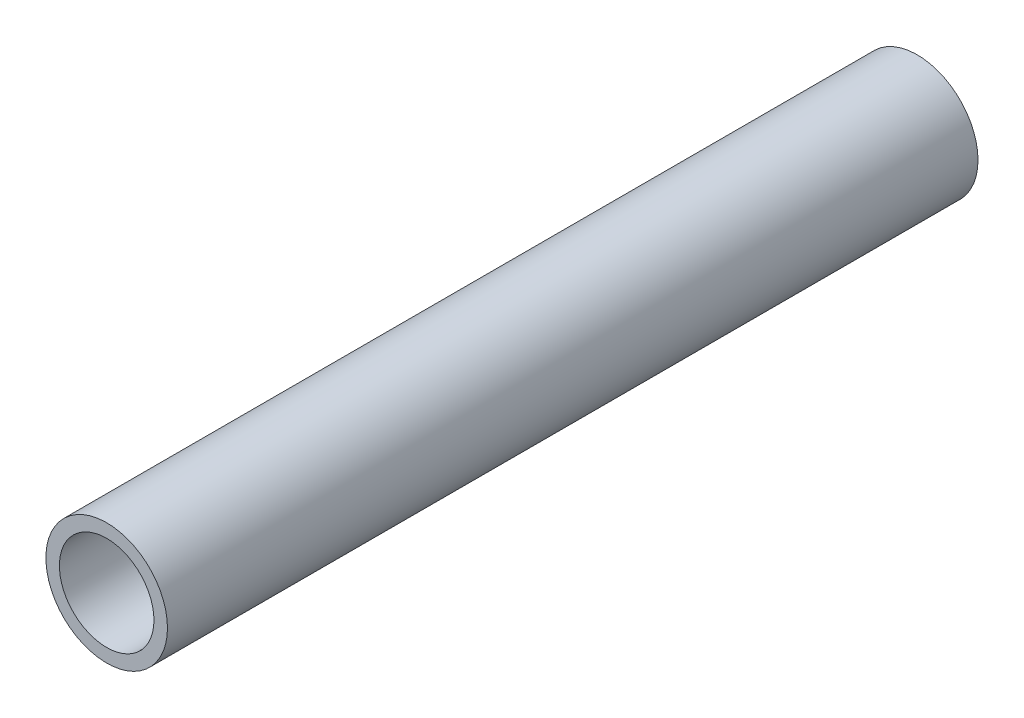
SolidWorks part; units mm, degrees
material "Copper"
ref_plane "Спереди" through (0, 0, 0) normal (0, 0, 1) x (1, 0, 0)
ref_plane "Сверху" through (0, 0, 0) normal (0, 1, 0) x (1, 0, 0)
ref_plane "Справа" through (0, 0, 0) normal (1, 0, 0) x (0, 0, -1)
sketch "Sketch1" plane through (0, 0, 0) normal (0, 0, 1) x (1, 0, 0)
  circle A0 centre (0, 0) radius 3.5
  circle A1 centre (0, 0) radius 4.5
  dimension "D1" = 1
  dimension "D2" = 7
extrude "Boss-Extrude1" add sketch "Sketch1" along normal blind 60
